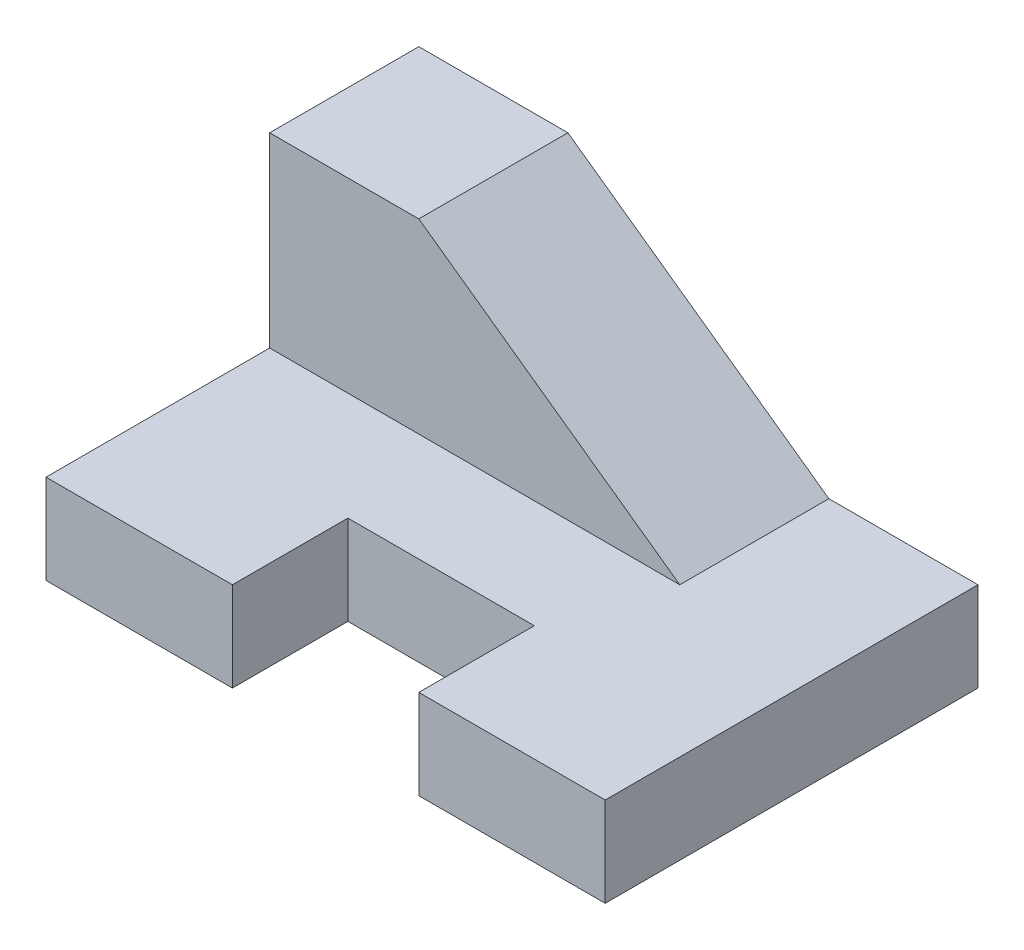
SolidWorks part; units mm, degrees
ref_plane "Front Plane" through (0, 0, 0) normal (0, 0, 1) x (1, 0, 0)
ref_plane "Top Plane" through (0, 0, 0) normal (0, 1, 0) x (1, 0, 0)
ref_plane "Right Plane" through (0, 0, 0) normal (1, 0, 0) x (0, 0, -1)
sketch "Sketch2" plane through (0, 0, 0) normal (0, 1, 0) x (1, 0, 0)
  line L0 (-37.5, 25) -> (37.5, 25)
  line L1 (37.5, 25) -> (37.5, -25)
  line L2 (37.5, -25) -> (12.5, -25)
  line L3 (12.5, -25) -> (12.5, -9.5109)
  line L4 (12.5, -9.5109) -> (-12.5, -9.5109)
  line L5 (-12.5, -9.5109) -> (-12.5, -25)
  line L6 (-12.5, -25) -> (-37.5, -25)
  line L7 (-37.5, -25) -> (-37.5, 25)
  point P6 (0, 25)
  dimension "D1" = 75
  dimension "D2" = 50
  dimension "D3" = 25
  dimension "D4" = 25
  dimension "D5" = 50
  dimension "D6" = 25
  dimension "D7" = 37.5
extrude "Boss-Extrude1" add sketch "Sketch2" along normal blind 12
sketch "Sketch4" plane through (0, 0, -25) normal (0, 0, -1) x (-1, 0, 0)
  line L16 (37.5, 12) -> (37.5, 37)
  line L17 (37.5, 37) -> (17.5, 37)
  line L18 (17.5, 37) -> (-17.5, 12)
  line L19 (-37.5, 12) -> (37.5, 12) construction
  line L20 (-17.5, 12) -> (37.5, 12)
  dimension "D1" = 25
  dimension "D2" = 20
  dimension "D3" = 55
extrude "Boss-Extrude4" add sketch "Sketch4" against normal blind 20
